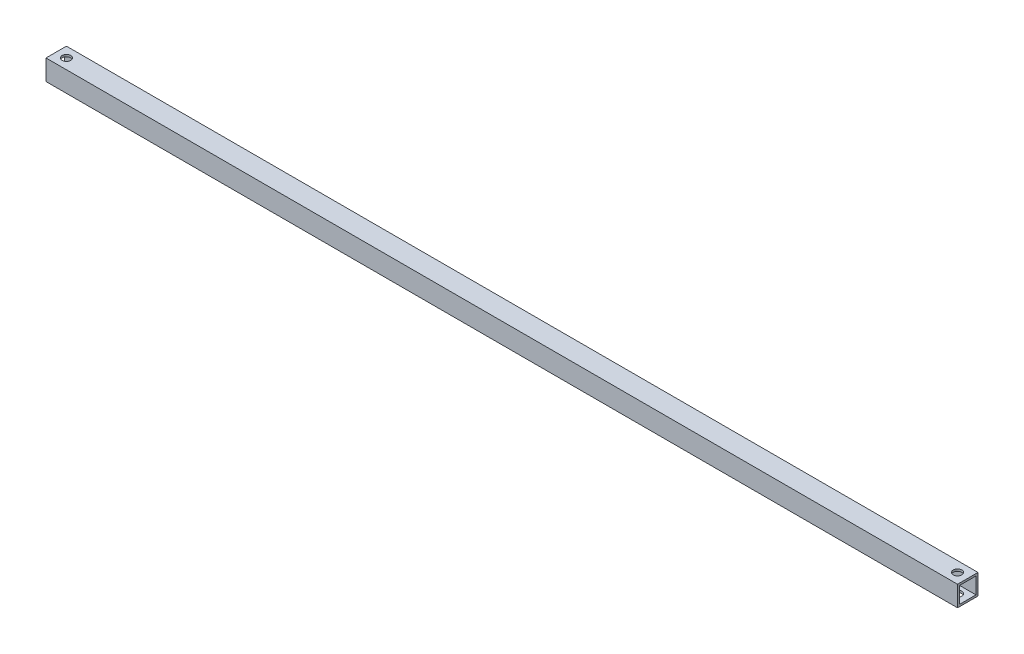
SolidWorks part; units mm, degrees
material "5052-H34"
ref_plane "正面" through (0, 0, 0) normal (0, 0, 1) x (1, 0, 0)
ref_plane "平面" through (0, 0, 0) normal (0, 1, 0) x (1, 0, 0)
ref_plane "右側面" through (0, 0, 0) normal (1, 0, 0) x (0, 0, -1)
sketch "ｽｹｯﾁ1" plane through (0, 0, 0) normal (1, 0, 0) x (0, -1, 0)
  line L1 (-5, 5) -> (5, 5)
  line L2 (-5, 5) -> (-5, -5)
  line L3 (-5, -5) -> (5, -5)
  line L4 (5, 5) -> (5, -5)
  line L5 (-5, 5) -> (5, -5) construction
  line L6 (-5, -5) -> (5, 5) construction
  point P0 (0, 0)
  dimension "D1" = 10
  dimension "D2" = 10
extrude "押し出し-薄板1" add sketch "ｽｹｯﾁ1" along normal blind 445.5861 thin
sketch "ｽｹｯﾁ2" plane through (0, 5, 0) normal (0, 1, 0) x (1, 0, 0)
  line L0 (222.793, 5) -> (222.793, -5) construction
  line L1 (445.5861, 5) -> (0, 5) construction
  line L2 (445.5861, -5) -> (0, -5) construction
  line L3 (0, 0) -> (5, 0) construction
  line L4 (445.5861, 0) -> (440.5861, 0) construction
  circle A0 centre (5, 0) radius 2.1
  circle A1 centre (440.5861, 0) radius 2.1
  dimension "D1" = 4.2
  dimension "D2" = 5
extrude "ｶｯﾄ - 押し出し1" cut sketch "ｽｹｯﾁ2" against normal through all
equation "\"D1@押し出し-薄板1\"=sqr(195^2+389.5^2)+10"
